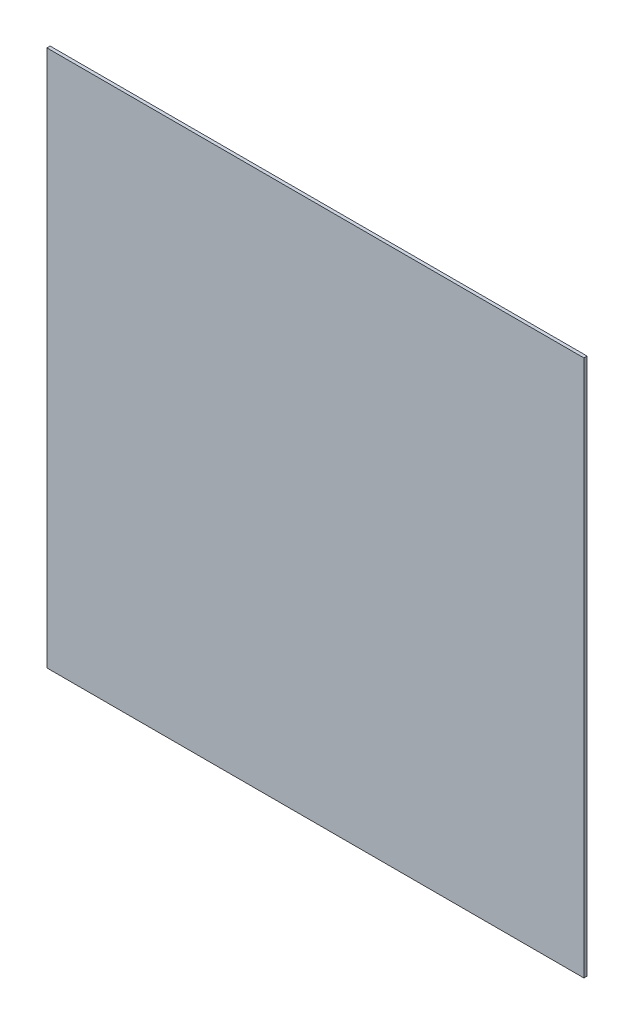
SolidWorks part; units mm, degrees
ref_plane "Front Plane" through (0, 0, 0) normal (0, 0, 1) x (1, 0, 0)
ref_plane "Top Plane" through (0, 0, 0) normal (0, 1, 0) x (1, 0, 0)
ref_plane "Right Plane" through (0, 0, 0) normal (1, 0, 0) x (0, 0, -1)
sketch "Sketch1" plane through (0, 0, 0) normal (0, 0, 1) x (1, 0, 0)
  line L1 (-15, -15) -> (15, -15)
  line L2 (-15, -15) -> (-15, 15)
  line L3 (-15, 15) -> (15, 15)
  line L4 (15, -15) -> (15, 15)
  line L5 (0, 15) -> (0, -15) construction
  line L6 (-15, 0) -> (15, 0) construction
  point P0 (0, 0)
  dimension "D1" = 30
  dimension "D2" = 30
extrude "Boss-Extrude1" add sketch "Sketch1" along normal blind 0.18
